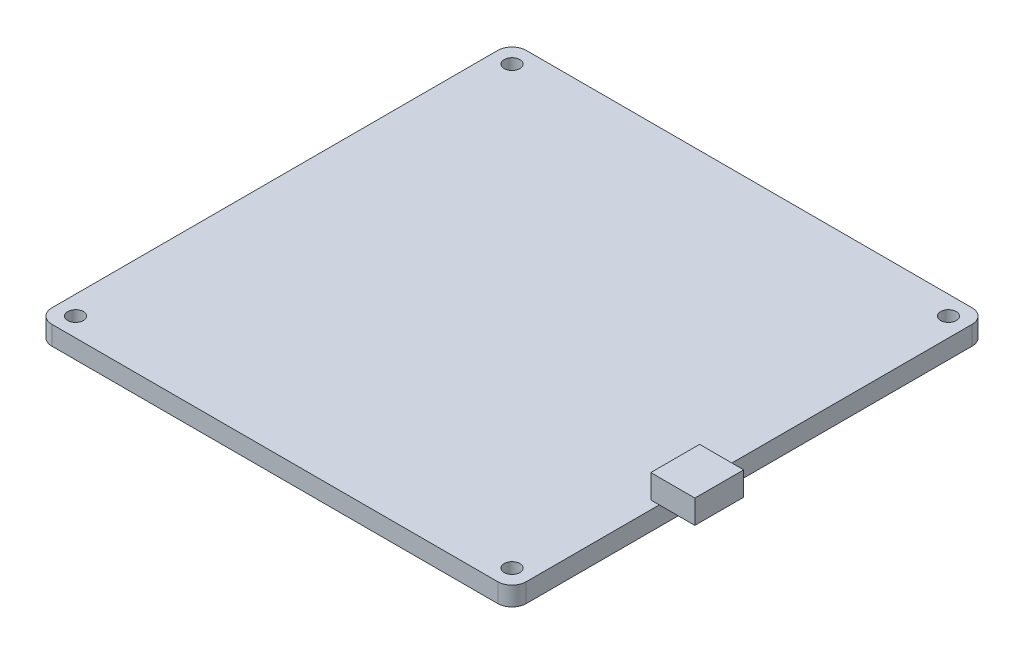
SolidWorks part; units mm, degrees
ref_plane "前视基准面" through (0, 0, 0) normal (0, 0, 1) x (1, 0, 0)
ref_plane "上视基准面" through (0, 0, 0) normal (0, 1, 0) x (1, 0, 0)
ref_plane "右视基准面" through (0, 0, 0) normal (1, 0, 0) x (0, 0, -1)
other "Configuration Table"
sketch "草图1" plane through (0, 0, 0) normal (0, 1, 0) x (1, 0, 0)
  line L1 (-50, 50) -> (50, 50)
  line L2 (-50, 50) -> (-50, -50)
  line L3 (-50, -50) -> (50, -50)
  line L4 (50, 50) -> (50, -50)
  line L5 (-50, 50) -> (50, -50) construction
  line L6 (-50, -50) -> (50, 50) construction
  circle A0 centre (-46, 46) radius 1.65
  circle A1 centre (46, 46) radius 1.65
  circle A2 centre (46, -46) radius 1.65
  circle A3 centre (-46, -46) radius 1.65
  point P0 (0, 0)
  point P17 (0, 0)
  dimension "D2" = 3.3
  dimension "D1" = 100
  dimension "D3" = 4
  dimension "D4" = 4
extrude "凸台-拉伸1" add sketch "草图1" along normal blind 4
fillet "圆角1" radius 3 4 edges at (50, 2, -50) (50, 2, 50) (-50, 2, 50) (-50, 2, -50)
sketch "草图2" plane through (0, 4, 0) normal (0, 1, 0) x (1, 0, 0)
  line L0 (47, 50) -> (-47, 50) construction
  line L1 (48.2, -8.65) -> (57.5, -8.65)
  line L2 (48.2, -8.65) -> (48.2, -18.95)
  line L3 (48.2, -18.95) -> (57.5, -18.95)
  line L4 (57.5, -8.65) -> (57.5, -18.95)
  line L5 (48.2, -8.65) -> (57.5, -18.95) construction
  line L6 (48.2, -18.95) -> (57.5, -8.65) construction
  line L8 (50, -47) -> (50, 47) construction
  point P0 (52.85, -13.8)
  dimension "D1" = 63.8
  dimension "D2" = 10.3
  dimension "D3" = 9.3
  dimension "D4" = 1.8
extrude "凸台-拉伸2" add sketch "草图2" along normal blind 5
